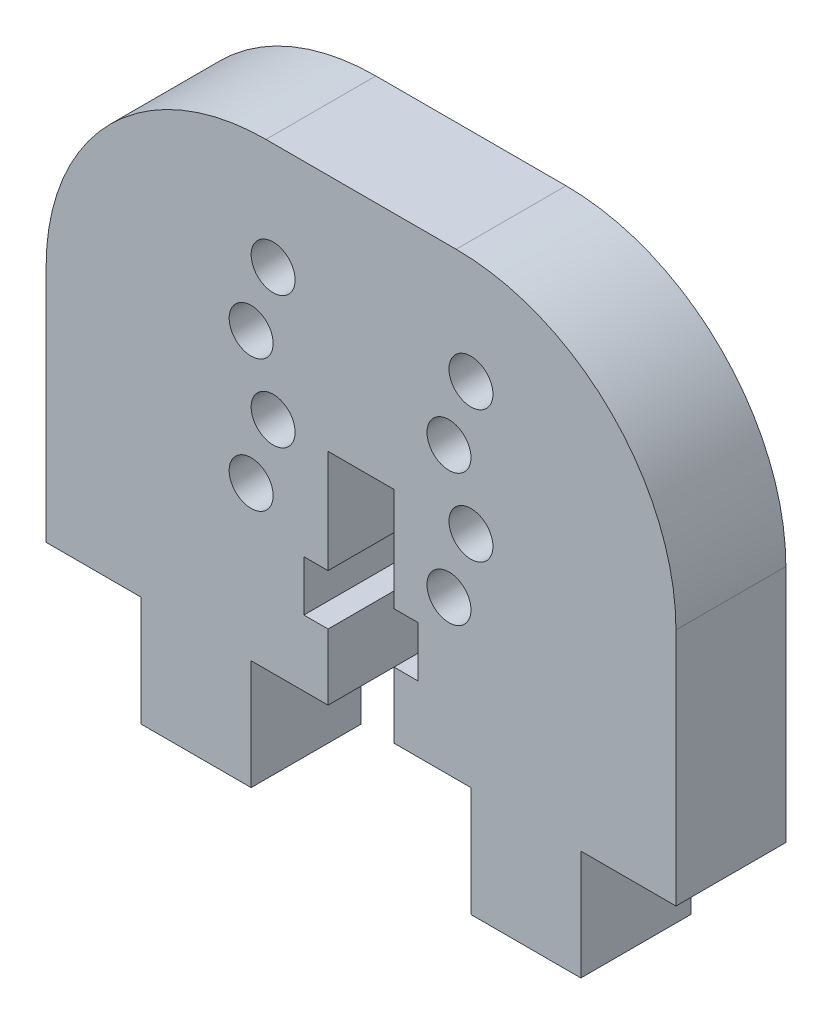
SolidWorks part; units mm, degrees
ref_plane "Front Plane" through (0, 0, 0) normal (0, 0, 1) x (1, 0, 0)
ref_plane "Top Plane" through (0, 0, 0) normal (0, 1, 0) x (1, 0, 0)
ref_plane "Right Plane" through (0, 0, 0) normal (1, 0, 0) x (0, 0, -1)
sketch "Sketch1" plane through (0, 0, 0) normal (0, 0, 1) x (1, 0, 0)
  line L0 (0, 0) -> (0, -10.438) construction
  line L1 (-14.3267, -10.438) -> (14.3267, -10.438)
  line L2 (-14.3267, -10.438) -> (-14.3267, 10.438)
  line L3 (-14.3267, 10.438) -> (14.3267, 10.438)
  line L4 (14.3267, -10.438) -> (14.3267, 10.438)
  line L5 (-14.3267, -10.438) -> (14.3267, 10.438) construction
  line L6 (-14.3267, 10.438) -> (14.3267, -10.438) construction
  line L7 (-4, -0.438) -> (-4, -9.4486) construction
  line L8 (-5, -3.438) -> (-5, -9.4486) construction
  line L9 (4, -3.438) -> (4, 2.562) construction
  line L10 (5, -0.438) -> (5, 5.562) construction
  line L11 (-5, -3.438) -> (4, -3.438) construction
  circle A0 centre (-5, -3.438) radius 1
  circle A1 centre (-4, -0.438) radius 1
  circle A2 centre (-5, 2.562) radius 1
  circle A3 centre (-4, 5.562) radius 1
  circle A4 centre (4, -3.438) radius 1
  circle A5 centre (5, -0.438) radius 1
  circle A6 centre (4, 2.562) radius 1
  circle A7 centre (5, 5.562) radius 1
  point P0 (0, 0)
  line B0 (-2.6, -7.438) -> (-2.6, -5.138)
  line B1 (1.5, -5.138) -> (1.5, -0.438)
  line B2 (-1.5, -0.438) -> (-1.5, -5.138)
  line B3 (-2.6, -5.138) -> (-1.5, -5.138)
  line B4 (0, -10.438) -> (0, 0.7828) construction
  line B5 (-1.5, -10.438) -> (-5, -10.438)
  line B6 (-5, -15.438) -> (-10, -15.438)
  line B7 (-10, -15.438) -> (-10, -10.438)
  line B8 (-5, -15.438) -> (-5, -10.438)
  line B9 (1.5, -10.438) -> (5, -10.438)
  line B10 (5, -10.438) -> (5, -15.438)
  line B11 (5, -15.438) -> (10, -15.438)
  line B12 (10, -15.438) -> (10, -10.438)
  line B13 (-1.5, -10.438) -> (1.5, -10.438) construction
  line B14 (1.5, -10.438) -> (1.5, -7.438)
  line B15 (1.5, -5.138) -> (2.6, -5.138)
  line B16 (2.6, -7.438) -> (1.5, -7.438)
  line B17 (1.5, -0.438) -> (-1.5, -0.438)
  line B18 (-1.5, -7.438) -> (-2.6, -7.438)
  line B19 (2.6, -5.138) -> (2.6, -7.438)
  line B20 (-1.5, -7.438) -> (-1.5, -10.438)
  line B21 (0, -0.438) -> (0, -10.438) construction
  dimension "D1" = 5
  dimension "D5" = 2
  dimension "D2" = 7
  dimension "D3" = 3
  dimension "D4" = 4
  dimension "D6" = 3
  dimension "D7" = 3
  dimension "D8" = 9
  dimension "D9" = 9
sketch_block_instance "Insert M3 plots ep 5mm-1"
sketch_block "Insert M3 plots ep 5mm" parameters "D1"=10, "D2"=5, "D3"=5
sketch_block_instance "Decoupe Insert M3-4"
sketch_block "Block1" parameters "D1"=5.2, "D2"=3, "D3"=2.3, "D4"=3, "D5"=10
extrude "Boss-Extrude1" add sketch "Sketch1" along normal blind 5 contours B20 B18 B0 B3 B2 B17 B1 B15 B19 B16 B14 L1 L4 L3 L2 A7 A6 A5 A4 A3 A2 A1 A0 | B6 B8 L1 B7 | B11 B12 L1 B10
fillet "Fillet1" radius 10 2 edges at (14.3267, 10.438, 2.5) (-14.3267, 10.438, 2.5)
